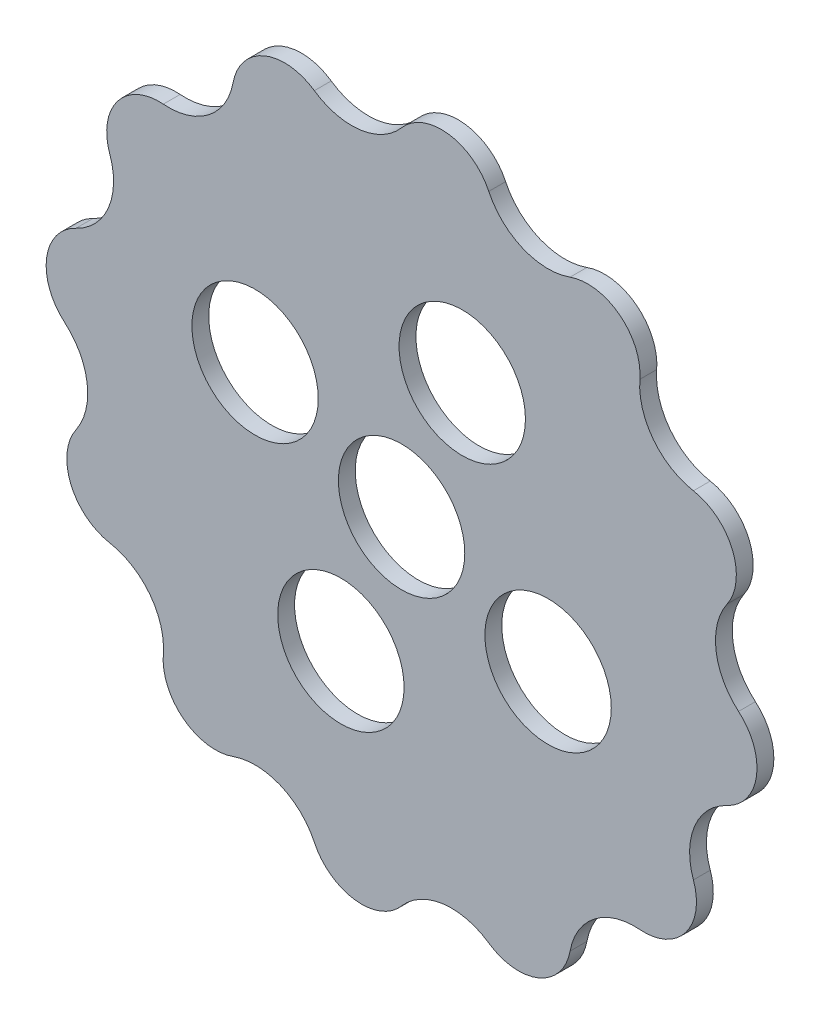
SolidWorks part; units mm, degrees
ref_plane "Alzado" through (0, 0, 0) normal (0, 0, 1) x (1, 0, 0)
ref_plane "Planta" through (0, 0, 0) normal (0, 1, 0) x (1, 0, 0)
ref_plane "Vista lateral" through (0, 0, 0) normal (1, 0, 0) x (0, 0, -1)
sketch "Croquis3" plane through (0, 0, 0) normal (0, 0, 1) x (1, 0, 0)
  circle A0 centre (0, 0) radius 85
  dimension "D1" = 170
extrude "Saliente-Extruir1" add sketch "Croquis3" along normal blind 4 contours A0
sketch "Croquis4" plane through (0, 0, 4) normal (0, 0, 1) x (1, 0, 0)
  line L0 (0, 80) -> (20.7055, 77.2741) construction
  line L1 (20.7055, 77.2741) -> (40, 69.282) construction
  line L2 (0, 0) -> (0, 85) construction
  line L3 (0, 0) -> (42.5, 73.6122) construction
  line L4 (0, 0) -> (9.4719, 71.9461) construction
  arc A0 (0, 80) -> (20.7055, 77.2741) centre (9.4719, 71.9461) cw
  arc A1 (20.7055, 77.2741) -> (40, 69.282) centre (34.7713, 83.9453) ccw
  circle A2 centre (0, 0) radius 85 construction
  arc A3 (20.7055, 77.2741) -> (40, 69.282) centre (0, 0) ccw
  arc A4 (40, 69.282) -> (56.5685, 56.5685) centre (44.1759, 57.5712) cw
  arc A5 (56.5685, 56.5685) -> (69.282, 40) centre (72.0855, 55.3131) ccw
  arc A6 (69.282, 40) -> (77.2741, 20.7055) centre (67.0431, 27.7701) cw
  arc A7 (77.2741, 20.7055) -> (80, 0) centre (90.0844, 11.8598) ccw
  arc A8 (80, 0) -> (77.2741, -20.7055) centre (71.9461, -9.4719) cw
  arc A9 (77.2741, -20.7055) -> (69.282, -40) centre (83.9453, -34.7713) ccw
  arc A10 (69.282, -40) -> (56.5685, -56.5685) centre (57.5712, -44.1759) cw
  arc A11 (56.5685, -56.5685) -> (40, -69.282) centre (55.3131, -72.0855) ccw
  arc A12 (40, -69.282) -> (20.7055, -77.2741) centre (27.7701, -67.0431) cw
  arc A13 (20.7055, -77.2741) -> (0, -80) centre (11.8598, -90.0844) ccw
  arc A14 (0, -80) -> (-20.7055, -77.2741) centre (-9.4719, -71.9461) cw
  arc A15 (-20.7055, -77.2741) -> (-40, -69.282) centre (-34.7713, -83.9453) ccw
  arc A16 (-40, -69.282) -> (-56.5685, -56.5685) centre (-44.1759, -57.5712) cw
  arc A17 (-56.5685, -56.5685) -> (-69.282, -40) centre (-72.0855, -55.3131) ccw
  arc A18 (-69.282, -40) -> (-77.2741, -20.7055) centre (-67.0431, -27.7701) cw
  arc A19 (-77.2741, -20.7055) -> (-80, 0) centre (-90.0844, -11.8598) ccw
  arc A20 (-80, 0) -> (-77.2741, 20.7055) centre (-71.9461, 9.4719) cw
  arc A21 (-77.2741, 20.7055) -> (-69.282, 40) centre (-83.9453, 34.7713) ccw
  arc A22 (-69.282, 40) -> (-56.5685, 56.5685) centre (-57.5712, 44.1759) cw
  arc A23 (-56.5685, 56.5685) -> (-40, 69.282) centre (-55.3131, 72.0855) ccw
  arc A24 (-40, 69.282) -> (-20.7055, 77.2741) centre (-27.7701, 67.0431) cw
  arc A25 (-20.7055, 77.2741) -> (0, 80) centre (-11.8598, 90.0844) ccw
  circle A26 centre (0, 0) radius 85
  circle M7 centre (0, 0) radius 85
  dimension "D1" = 160
  dimension "D2" = 30
  dimension "D3" = 72.5669
  dimension "D4" = 12
extrude "Cortar-Extruir1" cut sketch "Croquis4" against normal blind 4 contours A1 A4 A0 M7 | A24 A3 A0 M7 | A3 A25 | A3 A24 A22 M7 | A3 A23 | A3 A22 A20 M7 | A3 A21 | A3 A20 A18 M7 | A3 A19 | A3 A18 A16 M7 | A3 A17 | A3 A16 A14 M7 | A3 A15 | A3 A14 A12 M7 | A3 A13 | A3 A11 | A3 A12 A10 M7 | A3 A10 A8 M7 | A3 A9 | A3 A8 A6 M7 | A3 A7 | A3 A6 A4 M7 | A3 A5
sketch "Croquis5" plane through (0, 0, 4) normal (0, 0, 1) x (1, 0, 0)
  circle A0 centre (0, 0) radius 15
  dimension "D1" = 30
extrude "Cortar-Extruir2" cut sketch "Croquis5" against normal blind 4
sketch "Croquis6" plane through (0, 0, 4) normal (0, 0, 1) x (1, 0, 0)
  line L0 (0, 0) -> (28.8138, 69.5627) construction
  line L1 (0, 0) -> (14.4069, 34.7813) construction
  arc A0 (20.7055, 77.2741) -> (40, 69.282) centre (34.7713, 83.9453) ccw construction
  circle A1 centre (14.4069, 34.7813) radius 15
  circle A2 centre (0, 0) radius 37.6471 construction
  circle A3 centre (34.7813, -14.4069) radius 15
  circle A4 centre (-14.4069, -34.7813) radius 15
  circle A5 centre (-34.7813, 14.4069) radius 15
  dimension "D1" = 30
  dimension "D2" = 37.6471
extrude "Cortar-Extruir3" cut sketch "Croquis6" against normal blind 4
